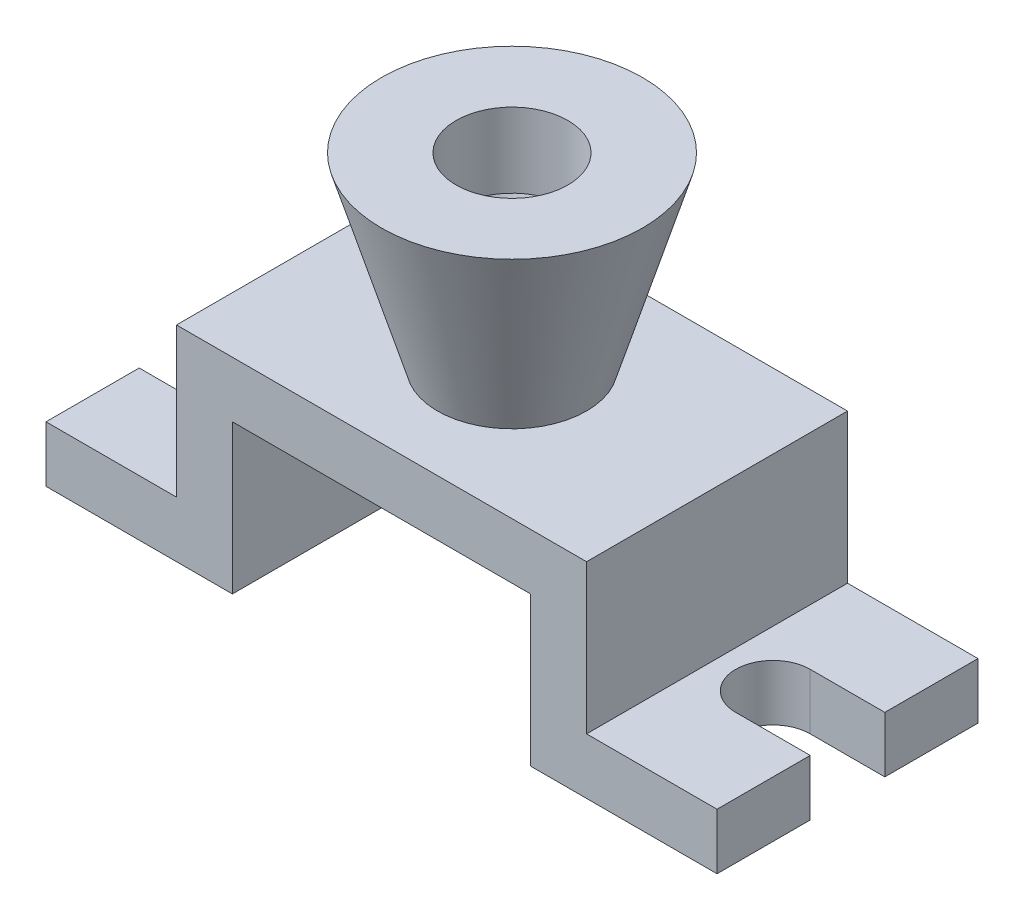
SolidWorks part; units mm, degrees
ref_plane "Front Plane" through (0, 0, 0) normal (0, 0, 1) x (1, 0, 0)
ref_plane "Top Plane" through (0, 0, 0) normal (0, 1, 0) x (1, 0, 0)
ref_plane "Right Plane" through (0, 0, 0) normal (1, 0, 0) x (0, 0, -1)
sketch "Sketch2" plane through (0, 0, 0) normal (0, 0, 1) x (1, 0, 0)
  line L0 (-90, 0) -> (-40, 0)
  line L1 (-40, 0) -> (-40, 40)
  line L2 (-40, 40) -> (40, 40)
  line L3 (40, 40) -> (40, 0)
  line L4 (40, 0) -> (90, 0)
  line L5 (90, 0) -> (90, 15)
  line L6 (90, 15) -> (55, 15)
  line L7 (55, 15) -> (55, 55)
  line L8 (55, 55) -> (-55, 55)
  line L9 (-55, 55) -> (-55, 15)
  line L10 (-55, 15) -> (-90, 15)
  line L11 (-90, 15) -> (-90, 0)
  point P12 (0, 40)
  point P14 (105.3982, 16.3274)
  point P15 (69.292, 55)
  point P16 (41.6814, 0)
  point P17 (121.3274, 15)
  dimension "D1" = 15
  dimension "D2" = 55
  dimension "D3" = 50
  dimension "D4" = 15
  dimension "D5" = 15
  dimension "D6" = 15
  dimension "D7" = 80
extrude "Boss-Extrude1" add sketch "Sketch2" along normal mid plane 70
sketch "Sketch4" plane through (0, 55, 0) normal (0, 1, 0) x (1, 0, 0)
  line L0 (0, 0) -> (0, 35) construction
  line L1 (55, 35) -> (-55, 35) construction
  line L2 (-70, 10) -> (-90, 10)
  line L3 (-90, -35) -> (-90, 35) construction
  line L4 (-70, -10) -> (-90, -10)
  line L5 (-90, -10) -> (-90, 10)
  line L6 (90, -10) -> (90, 10)
  line L7 (70, -10) -> (90, -10)
  line L8 (70, 10) -> (90, 10)
  circle A0 centre (0, 0) radius 8
  arc A1 (-70, -10) -> (-70, 10) centre (-70, 0) ccw
  arc A2 (70, -10) -> (70, 10) centre (70, 0) cw
  dimension "D1" = 16
  dimension "D2" = 20
  dimension "D3" = 70
extrude "Cut-Extrude1" cut sketch "Sketch4" against normal through all
sketch "Sketch5" plane through (0, 0, 0) normal (0, 0, 1) x (1, 0, 0)
  line L0 (0, 55) -> (0, 105) construction
  line L1 (55, 55) -> (-55, 55) construction
  line L3 (-35, 105) -> (-20, 55)
  line L4 (-20, 55) -> (-8, 55)
  line L5 (-35, 105) -> (-15, 105)
  line L6 (-8, 55) -> (-8, 70)
  line L7 (-8, 70) -> (-15, 85)
  line L8 (-15, 85) -> (-15, 105)
  line L9 (-40, 40) -> (40, 40) construction
  dimension "D1" = 50
  dimension "D2" = 70
  dimension "D3" = 30
  dimension "D4" = 40
  dimension "D5" = 30
  dimension "D6" = 15
  dimension "D7" = 16
revolve "Revolve1" add sketch "Sketch5" angle 360 about L0
